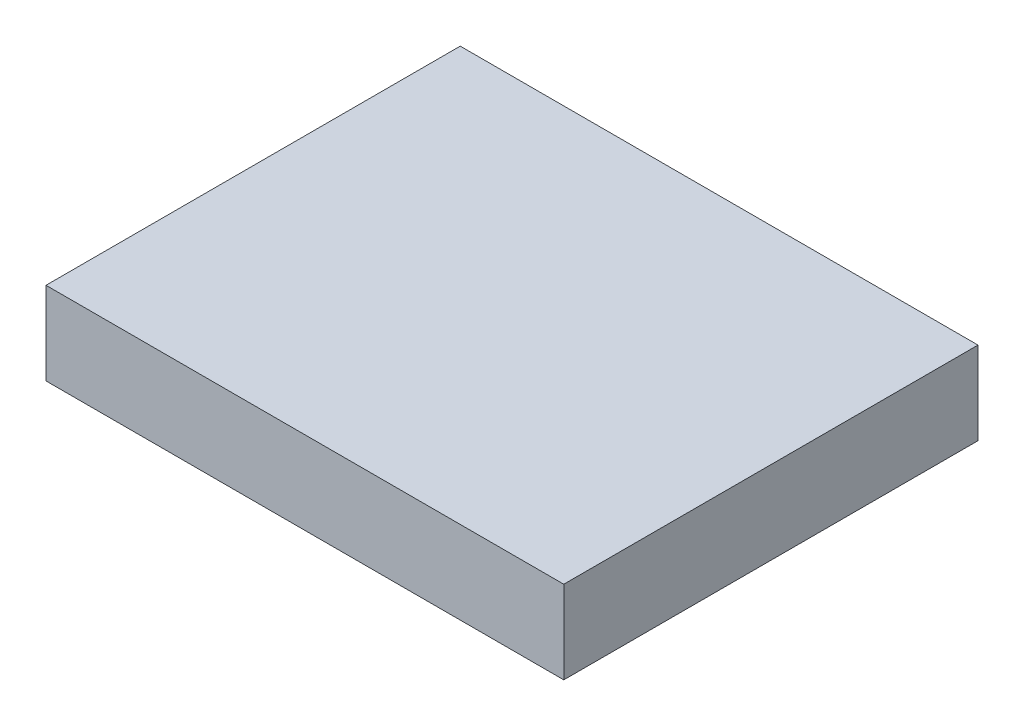
SolidWorks part; units mm, degrees
ref_plane "Front Plane" through (0, 0, 0) normal (0, 0, 1) x (1, 0, 0)
ref_plane "Top Plane" through (0, 0, 0) normal (0, 1, 0) x (1, 0, 0)
ref_plane "Right Plane" through (0, 0, 0) normal (1, 0, 0) x (0, 0, -1)
sketch "Sketch1" plane through (0, 0, 0) normal (0, 1, 0) x (1, 0, 0)
  line L1 (-12.5, -10) -> (12.5, -10)
  line L2 (-12.5, -10) -> (-12.5, 10)
  line L3 (-12.5, 10) -> (12.5, 10)
  line L4 (12.5, -10) -> (12.5, 10)
  line L5 (-12.5, -10) -> (12.5, 10) construction
  line L6 (-12.5, 10) -> (12.5, -10) construction
  point P0 (0, 0)
  dimension "D1" = 25
  dimension "D2" = 20
extrude "Boss-Extrude1" add sketch "Sketch1" along normal blind 4
